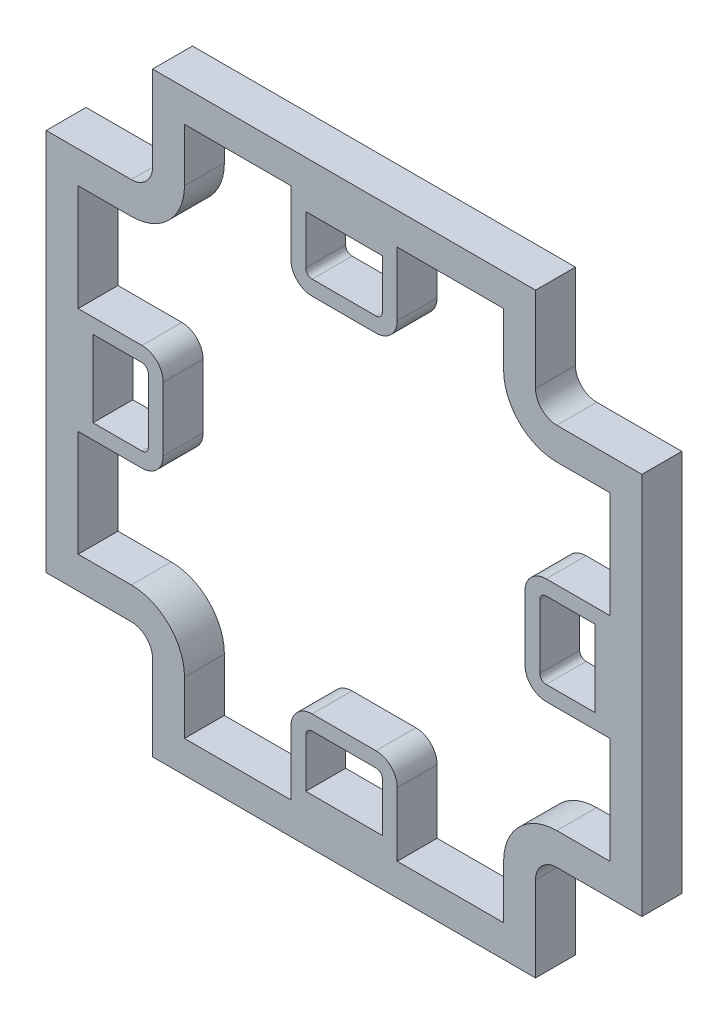
SolidWorks part; units mm, degrees
material "PBT General Purpose"
ref_plane "Front Plane" through (0, 0, 0) normal (0, 0, 1) x (1, 0, 0)
ref_plane "Top Plane" through (0, 0, 0) normal (0, 1, 0) x (1, 0, 0)
ref_plane "Right Plane" through (0, 0, 0) normal (1, 0, 0) x (0, 0, -1)
sketch "Sketch1" plane through (0, 0, 0) normal (0, 0, 1) x (1, 0, 0)
  line L0 (71, 100) -> (63, 100)
  line L1 (63, 110) -> (63, 54) construction
  line L2 (63, 100) -> (63, 64)
  line L3 (63, 64) -> (71, 64)
  line L4 (73, 62) -> (73, 54)
  line L5 (63, 54) -> (119, 54) construction
  line L6 (73, 54) -> (109, 54)
  line L7 (109, 54) -> (109, 62)
  line L8 (111, 64) -> (119, 64)
  line L9 (119, 54) -> (119, 110) construction
  line L10 (119, 64) -> (119, 100)
  line L11 (119, 100) -> (111, 100)
  line L12 (109, 102) -> (109, 110)
  line L13 (119, 110) -> (63, 110) construction
  line L14 (109, 110) -> (73, 110)
  line L15 (73, 110) -> (73, 102)
  circle A0 centre (68, 105) radius 2.15 construction
  circle A1 centre (68, 59) radius 2.15 construction
  circle A2 centre (114, 59) radius 2.15 construction
  circle A3 centre (114, 105) radius 2.15 construction
  arc A4 (71, 100) -> (73, 102) centre (71, 102) ccw
  arc A5 (111, 100) -> (109, 102) centre (111, 102) cw
  arc A6 (109, 62) -> (111, 64) centre (111, 62) cw
  arc A7 (73, 62) -> (71, 64) centre (71, 62) ccw
  dimension "D1" = 5
  dimension "D2" = 5
  dimension "D4" = 5
  dimension "D5" = 5
  dimension "D6" = 5
  dimension "D9" = 2
  dimension "D3" = 5
  dimension "D7" = 5
  dimension "D8" = 5
extrude "Extrude-Thin1" add sketch "Sketch1" along normal blind 3.75 thin thin type one direction reverse wall 3
sketch "Sketch2" plane through (0, 0, 0) normal (0, 0, 1) x (1, 0, 0)
  line L0 (66, 87) -> (72, 87)
  line L1 (66, 97) -> (66, 67) construction
  line L2 (74, 85) -> (74, 79)
  line L3 (72, 77) -> (66, 77)
  line L5 (110, 87) -> (116, 87)
  line L6 (116, 87) -> (116, 77)
  line L7 (116, 77) -> (110, 77)
  line L8 (108, 85) -> (108, 79)
  line L9 (116, 67) -> (116, 97) construction
  line L17 (76, 107) -> (76, 102)
  line L18 (106, 107) -> (76, 107)
  line L19 (106, 102) -> (106, 107)
  line L20 (116, 97) -> (111, 97)
  line L21 (116, 67) -> (116, 97)
  line L22 (111, 67) -> (116, 67)
  line L23 (106, 57) -> (106, 62)
  line L24 (76, 57) -> (106, 57)
  line L25 (76, 62) -> (76, 57)
  line L26 (66, 67) -> (71, 67)
  line L27 (66, 97) -> (66, 67)
  line L28 (71, 97) -> (66, 97)
  line L39 (66, 87) -> (66, 77)
  circle A0 centre (70, 82) radius 2.15 construction
  circle A1 centre (112, 82) radius 2.15 construction
  arc A2 (110, 87) -> (108, 85) centre (110, 85) ccw
  arc A3 (110, 77) -> (108, 79) centre (110, 79) cw
  arc A4 (74, 79) -> (72, 77) centre (72, 79) cw
  arc A5 (72, 87) -> (74, 85) centre (72, 85) cw
  arc A6 (71, 97) -> (76, 102) centre (71, 102) ccw
  arc A7 (71, 97) -> (76, 102) centre (71, 102) ccw
  arc A8 (106, 102) -> (111, 97) centre (111, 102) ccw
  arc A9 (106, 102) -> (111, 97) centre (111, 102) ccw
  arc A10 (111, 67) -> (106, 62) centre (111, 62) ccw
  arc A11 (111, 67) -> (106, 62) centre (111, 62) ccw
  arc A12 (76, 62) -> (71, 67) centre (71, 62) ccw
  arc A13 (76, 62) -> (71, 67) centre (71, 62) ccw
  point P18 (116, 88.1879)
  point P24 (107.1487, 76.912)
  dimension "D1" = 5
  dimension "D2" = 4
  dimension "D5" = 4
  dimension "D6" = 2
  dimension "D3" = 5
  dimension "D4" = 0
extrude "Extrude-Thin2" add sketch "Sketch2" along normal blind 3.75 thin
sketch "Sketch3" plane through (0, 0, 0) normal (0, 0, 1) x (1, 0, 0)
  line L0 (86, 107) -> (86, 101)
  line L1 (106, 107) -> (76, 107) construction
  line L2 (88, 99) -> (94, 99)
  line L3 (96, 101) -> (96, 107)
  line L4 (96, 107) -> (86, 107)
  line L5 (96, 57) -> (96, 63)
  line L6 (76, 57) -> (106, 57) construction
  line L7 (94, 65) -> (88, 65)
  line L8 (86, 63) -> (86, 57)
  line L9 (86, 57) -> (96, 57)
  circle A0 centre (91, 103) radius 2.15 construction
  circle A1 centre (91, 61) radius 2.15 construction
  arc A2 (96, 63) -> (94, 65) centre (94, 63) ccw
  arc A3 (88, 65) -> (86, 63) centre (88, 63) ccw
  arc A4 (86, 101) -> (88, 99) centre (88, 101) ccw
  arc A5 (94, 99) -> (96, 101) centre (94, 101) ccw
  point P24 (96, 99)
  dimension "D1" = 5
  dimension "D4" = 4
  dimension "D5" = 2
  dimension "D2" = 5
  dimension "D3" = 4
extrude "Extrude-Thin3" add sketch "Sketch3" along normal blind 3.75 thin thin type one direction reverse wall 1.4
